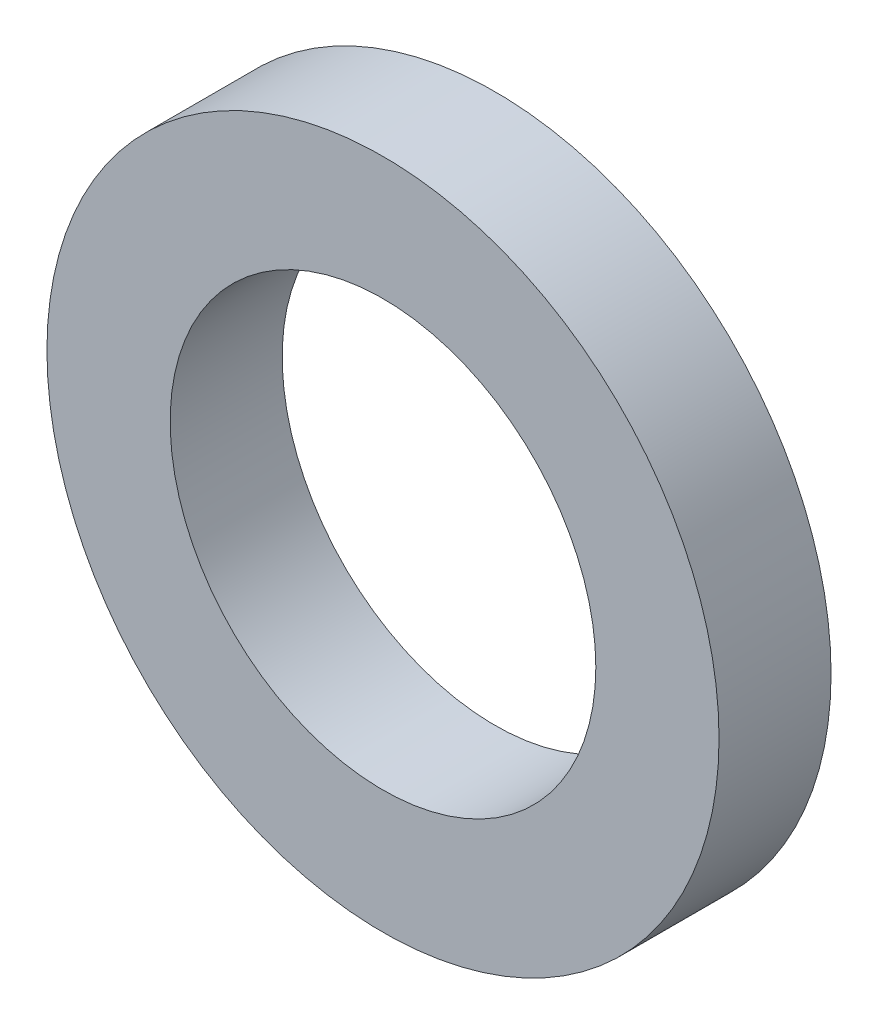
SolidWorks part; units mm, degrees
ref_plane "Front Plane" through (0, 0, 0) normal (0, 0, 1) x (1, 0, 0)
ref_plane "Top Plane" through (0, 0, 0) normal (0, 1, 0) x (1, 0, 0)
ref_plane "Right Plane" through (0, 0, 0) normal (1, 0, 0) x (0, 0, -1)
sketch "Sketch1" plane through (0, 0, 0) normal (0, 0, 1) x (1, 0, 0)
  circle A0 centre (0, 0) radius 3
  circle A1 centre (0, 0) radius 1.9
  dimension "D1" = 6
  dimension "D2" = 3.8
extrude "Boss-Extrude1" add sketch "Sketch1" along normal blind 1
